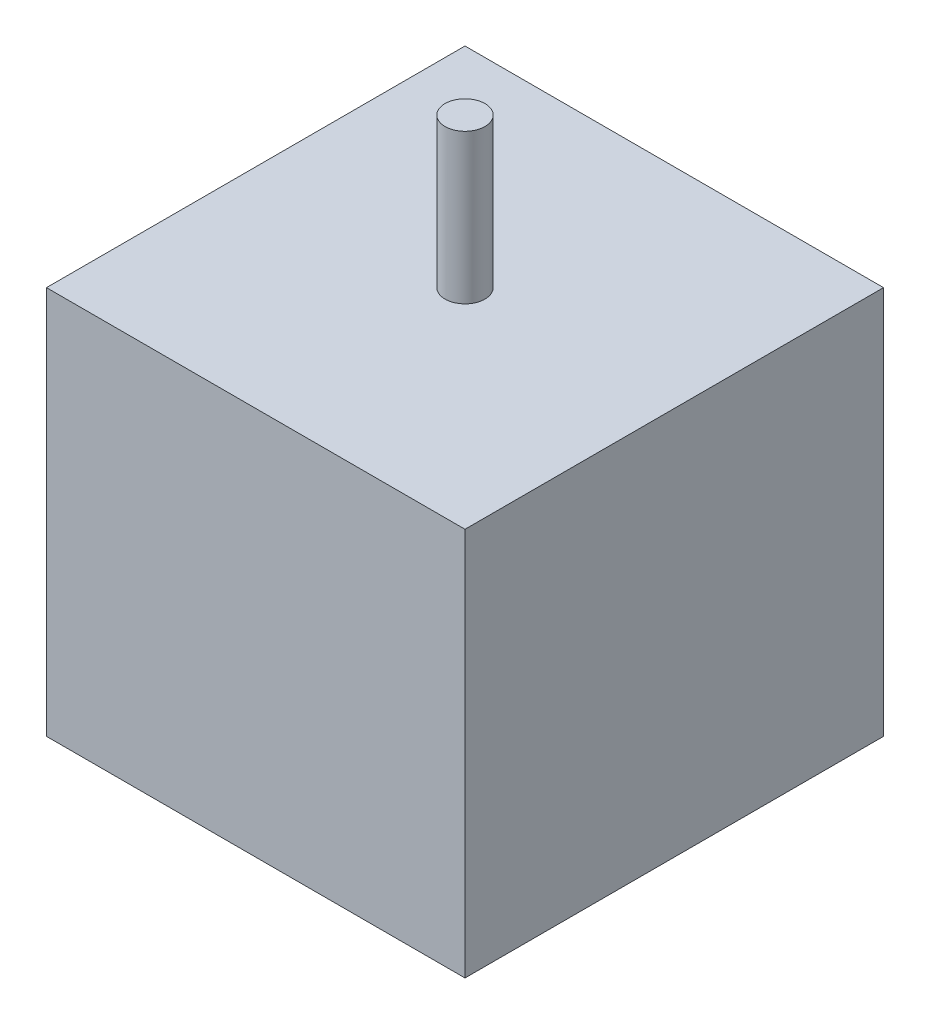
SolidWorks part; units mm, degrees
ref_plane "Plan de face" through (0, 0, 0) normal (0, 0, 1) x (1, 0, 0)
ref_plane "Plan de dessus" through (0, 0, 0) normal (0, 1, 0) x (1, 0, 0)
ref_plane "Plan de droite" through (0, 0, 0) normal (1, 0, 0) x (0, 0, -1)
sketch "Esquisse1" plane through (0, 0, 0) normal (0, 1, 0) x (1, 0, 0)
  line L1 (-21, -21) -> (21, -21)
  line L2 (-21, -21) -> (-21, 21)
  line L3 (-21, 21) -> (21, 21)
  line L4 (21, -21) -> (21, 21)
  line L5 (-21, -21) -> (21, 21) construction
  line L6 (-21, 21) -> (21, -21) construction
  point P0 (0, 0)
  dimension "D1" = 42
  dimension "D2" = 42
extrude "Boss.-Extru.1" add sketch "Esquisse1" along normal blind 39
ref_plane "Plan1" through (0, 39, 0) normal (0, 1, 0) x (1, 0, 0)
sketch "Esquisse3" plane through (0, 39, 0) normal (0, 1, 0) x (1, 0, 0)
  circle A0 centre (0, 0) radius 7.5
  point P3 (0, 0)
  dimension "D1" = 15
sketch "Esquisse4" plane through (0, 39, 0) normal (0, 1, 0) x (1, 0, 0)
  circle A0 centre (0, 0) radius 2
  dimension "D1" = 4
extrude "Boss.-Extru.2" add sketch "Esquisse4" along normal blind 15
